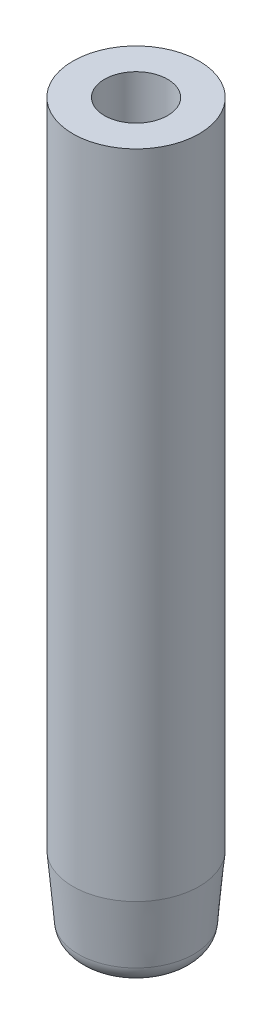
SolidWorks part; units mm, degrees
ref_plane "Front Plane" through (0, 0, 0) normal (0, 0, 1) x (1, 0, 0)
ref_plane "Top Plane" through (0, 0, 0) normal (0, 1, 0) x (1, 0, 0)
ref_plane "Right Plane" through (0, 0, 0) normal (1, 0, 0) x (0, 0, -1)
sketch "Sketch1" plane through (0, 0, 0) normal (0, 1, 0) x (1, 0, 0)
  circle A0 centre (0, 0) radius 6.35
  dimension "D1" = 12.7
extrude "Boss-Extrude1" add sketch "Sketch1" along normal blind 65.6
sketch "Sketch2" plane through (0, 65.6, 0) normal (0, 1, 0) x (1, 0, 0)
  circle A0 centre (0, 0) radius 3.175
  dimension "D1" = 6.35
extrude "Inner Chamber" cut sketch "Sketch2" against normal blind 60
sketch "Sketch4" plane through (0, 0, 0) normal (0, -1, 0) x (1, 0, 0)
  circle A0 centre (0, 0) radius 6.35
  dimension "D1" = 12.7
extrude "Head" add sketch "Sketch4" along normal blind 8 draft 5
fillet "Fillet1" radius 2 1 edges at (0, -8, -5.6501)
sketch "Sketch5" plane through (0, 0, 0) normal (0, 0, 1) x (1, 0, 0)
  line L0 (6.35, 0) -> (-6.35, 0) construction
  circle A0 centre (0, -5) radius 0.5
  dimension "D1" = 1
  dimension "D2" = 5
extrude "Cut-Extrude2" cut sketch "Sketch5" against normal blind 8
